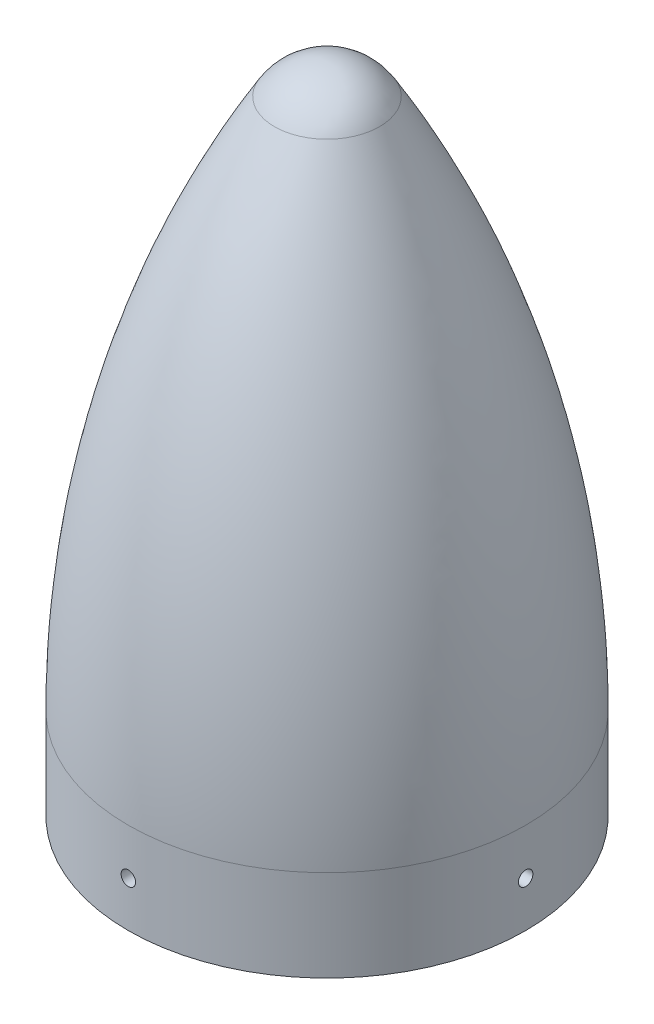
SolidWorks part; units mm, degrees
ref_plane "Front Plane" through (0, 0, 0) normal (0, 0, 1) x (1, 0, 0)
ref_plane "Top Plane" through (0, 0, 0) normal (0, 1, 0) x (1, 0, 0)
ref_plane "Right Plane" through (0, 0, 0) normal (1, 0, 0) x (0, 0, -1)
sketch "Sketch1" plane through (0, 0, 0) normal (0, 0, 1) x (1, 0, 0)
  line L3 (-41.275, 0) -> (-41.275, 94.9675) construction
  line L4 (0, 0) -> (0, 127.2583) construction
  line L5 (0, 116.6391) -> (0, 110.2891)
  line L6 (-41.275, 0) -> (-41.275, -18.95)
  line L7 (-41.275, -18.95) -> (-38.1, -18.95)
  line L9 (-34.925, 0) -> (-38.1, 0)
  line L10 (-38.1, 0) -> (-38.1, -18.95)
  line L11 (-41.275, 0) -> (-34.925, 0) construction
  line L12 (-34.925, 0) -> (0, 0) construction
  arc A0 (-10.9151, 110.4314) -> (0, 116.6391) centre (0, 103.9391) cw
  spline S0 degree 3 poles (-34.925, 0) (-35.7117, 37.0144) (-24.5116, 69.4551) (-5.8446, 109.5242) (0, 110.2891) knots 0 0 0 0 0.86028 1 1 1 1
  spline S2 degree 4 poles (-40.9693, -11.4895) (-40.9822, -11.2466) (-41.0072, -10.7613) (-41.0544, -9.7985) (-41.1162, -8.3427) (-41.1671, -6.9211) (-41.2072, -5.4594) (-41.2386, -4.0718) (-41.2579, -2.7997) (-41.2701, -1.7651) (-41.276, -0.1278) (-41.275, 0.4721) (-41.2687, 1.9121) (-41.2579, 2.7192) (-41.2464, 3.5639) (-41.2283, 4.5358) (-41.2007, 5.7342) (-41.1598, 7.1297) (-41.1008, 8.7354) (-41.0296, 10.3467) (-40.9463, 11.9588) (-40.8509, 13.5695) (-40.7435, 15.1799) (-40.6241, 16.7892) (-40.4598, 18.7997) (-40.2386, 21.2103) (-39.9456, 24.0193) (-39.5628, 27.2241) (-38.8092, 32.8221) (-36.9677, 43.9703) (-33.4913, 58.9237) (-28.3081, 74.6638) (-22.4871, 88.421) (-18.4288, 96.7676) (-16.1932, 101.0623) (-14.6574, 103.8912) (-13.7817, 105.4667) (-13.1957, 106.506) (-12.7072, 107.3626) (-12.3111, 108.051) (-11.9204, 108.7248) (-11.5265, 109.3984) (-11.0305, 110.2381) (-10.7524, 110.7053) (-10.167, 111.6822) (-9.756, 112.3581) (-9.2497, 113.1865) (-8.7818, 113.9428) (-8.2917, 114.729) (-7.8068, 115.4987) (-7.1874, 116.4733) (-6.4361, 117.6403) (-5.8, 118.6132) (-5.2857, 119.39) (-5.0271, 119.7781) knots 0 0 0 0 0 0.007003 0.014005 0.02801 0.041762 0.048638 0.055514 0.069266 0.076142 0.083018 0.094423 0.100125 0.105828 0.11153 0.117233 0.128638 0.140293 0.151949 0.163604 0.17526 0.186915 0.198571 0.210226 0.221881 0.245192 0.268503 0.291814 0.315125 0.408368 0.594855 0.734721 0.792998 0.83962 0.862931 0.874586 0.885991 0.891694 0.897396 0.903099 0.908801 0.914504 0.920206 0.926814 0.933421 0.940028 0.946636 0.953243 0.959851 0.966458 0.973065 0.986533 1 1 1 1 1 construction
  spline S3 degree 4 poles (-41.275, 0) (-41.275, 0.3305) (-41.2736, 0.8056) (-41.2687, 1.9121) (-41.2579, 2.7192) (-41.2464, 3.5639) (-41.2283, 4.5358) (-41.2007, 5.7342) (-41.1598, 7.1297) (-41.1008, 8.7354) (-41.0296, 10.3467) (-40.9463, 11.9588) (-40.8509, 13.5695) (-40.7435, 15.1799) (-40.6241, 16.7892) (-40.4598, 18.7997) (-40.2386, 21.2103) (-39.9456, 24.0193) (-39.5628, 27.2241) (-38.8092, 32.8221) (-36.9677, 43.9703) (-33.4913, 58.9237) (-28.3081, 74.6638) (-22.4871, 88.421) (-18.4288, 96.7676) (-16.1932, 101.0623) (-14.6574, 103.8912) (-13.7817, 105.4667) (-13.1957, 106.506) (-12.7072, 107.3626) (-12.3111, 108.051) (-11.9204, 108.7248) (-11.5265, 109.3984) (-11.1687, 110.0042) (-10.9996, 110.2893) (-10.9151, 110.4314) knots 0.083018 0.083018 0.083018 0.083018 0.083018 0.094423 0.100125 0.105828 0.11153 0.117233 0.128638 0.140293 0.151949 0.163604 0.17526 0.186915 0.198571 0.210226 0.221881 0.245192 0.268503 0.291814 0.315125 0.408368 0.594855 0.734721 0.792998 0.83962 0.862931 0.874586 0.885991 0.891694 0.897396 0.903099 0.908801 0.914504 0.920206 0.920206 0.920206 0.920206 0.920206
  dimension "D3" = 12.7
  dimension "D4" = 6.35
  dimension "D5" = 34.925
  dimension "D2" = 3.175
  dimension "D6" = 2.8451
  dimension "D7" = 7.1967
  dimension "D8" = 11.8129
  dimension "D9" = 10.9151
  dimension "D10" = 5.2311
  dimension "D11" = 47.4547
  dimension "D12" = 18.95
  dimension "D13" = 3.175
  dimension "D15" = 6.35
revolve "Revolve1" add sketch "Sketch1" angle 360 about L4
sketch "Sketch6" plane through (0, 0, 0) normal (0, 0, 1) x (1, 0, 0)
  line L0 (0, 0) -> (0, 119.6655) construction
ref_plane "Plane2" through (0, 0, 41.275) normal (0, 0, 1) x (1, 0, 0)
sketch "Sketch7" plane through (0, 0, 41.275) normal (0, 0, 1) x (1, 0, 0)
  line L0 (0, -200000) -> (0, 200119.6655) construction
  line L1 (0, -9.525) -> (0, 0) construction
  circle A0 centre (0, -9.525) radius 1.5
  dimension "D1" = 3
  dimension "D2" = 9.525
extrude "Cut-Extrude1" cut sketch "Sketch7" against normal blind 3.81
pattern_circular "CirPattern1" count 4 over 360 about axis through (0, 0, 0) along (0, -1, 0) of "Cut-Extrude1"
